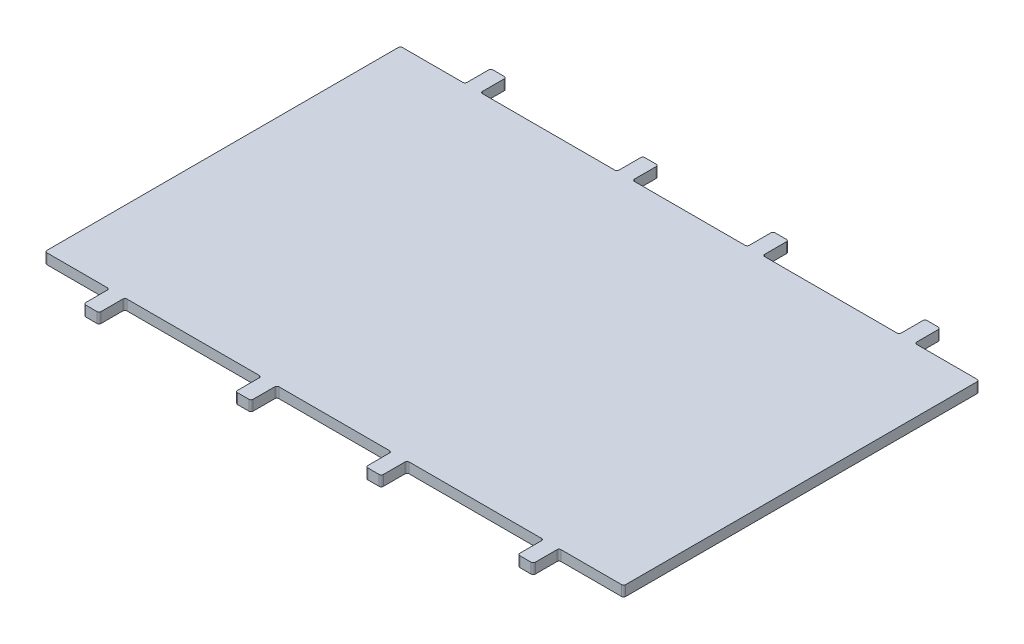
SolidWorks part; units mm, degrees
ref_plane "Front Plane" through (0, 0, 0) normal (0, 0, 1) x (1, 0, 0)
ref_plane "Top Plane" through (0, 0, 0) normal (0, 1, 0) x (1, 0, 0)
ref_plane "Right Plane" through (0, 0, 0) normal (1, 0, 0) x (0, 0, -1)
sketch "Sketch1" plane through (0, 0, 0) normal (0, 1, 0) x (1, 0, 0)
  line L1 (280, -172) -> (-280, -172)
  line L2 (280, -172) -> (280, 172)
  line L3 (280, 172) -> (-280, 172)
  line L4 (-280, -172) -> (-280, 172)
  line L5 (280, -172) -> (-280, 172) construction
  line L6 (280, 172) -> (-280, -172) construction
  point P0 (0, 0)
  dimension "D1" = 560
  dimension "D2" = 344
extrude "Boss-Extrude1" add sketch "Sketch1" along normal blind 10
sketch "Sketch2" plane through (0, 10, 0) normal (0, 1, 0) x (1, 0, 0)
  line L0 (-280, -172) -> (280, -172) construction
  line L1 (-70.5, -172) -> (-55.5, -172)
  line L2 (-70.5, -172) -> (-70.5, -197)
  line L3 (-70.5, -197) -> (-55.5, -197)
  line L4 (-55.5, -172) -> (-55.5, -197)
  line L5 (-210, -172) -> (-210, -197) construction
  line L6 (-202.5, -172) -> (-217.5, -172)
  line L7 (-202.5, -172) -> (-202.5, -197)
  line L8 (-202.5, -197) -> (-217.5, -197)
  line L9 (-217.5, -172) -> (-217.5, -197)
  line L10 (-63, -172) -> (-63, -197) construction
  dimension "D1" = 63
  dimension "D2" = 147
  dimension "D3" = 25
  dimension "D4" = 15
  dimension "D5" = 15
extrude "Boss-Extrude2" add sketch "Sketch2" against normal up to surface (10 mm away) up to face at (0, 0, 0)
mirror "Mirror4" about plane through (0, 0, 0) normal (1, 0, 0) of "Boss-Extrude2"
mirror "Mirror5" about plane through (0, 0, 0) normal (0, 0, 1) of "Mirror4", "Boss-Extrude2"
fillet "Fillet3" radius 2 36 edges at (-70.5, 5, -172) (-70.5, 5, -197) (-55.5, 5, -197) (-55.5, 5, -172) (55.5, 5, -172) (55.5, 5, -197) (70.5, 5, -197) (70.5, 5, -172) (202.5, 5, -172) (202.5, 5, -197) (217.5, 5, -197) (217.5, 5, -172) (280, 5, -172) (280, 5, 172) (217.5, 5, 172) (217.5, 5, 197) (202.5, 5, 197) (202.5, 5, 172) (70.5, 5, 172) (70.5, 5, 197) (55.5, 5, 197) (55.5, 5, 172) (-55.5, 5, 172) (-55.5, 5, 197) (-70.5, 5, 197) (-70.5, 5, 172) (-202.5, 5, 172) (-202.5, 5, 197) (-217.5, 5, 197) (-217.5, 5, 172) (-280, 5, 172) (-202.5, 5, -172) (-202.5, 5, -197) (-217.5, 5, -172) (-217.5, 5, -197) (-280, 5, -172)
